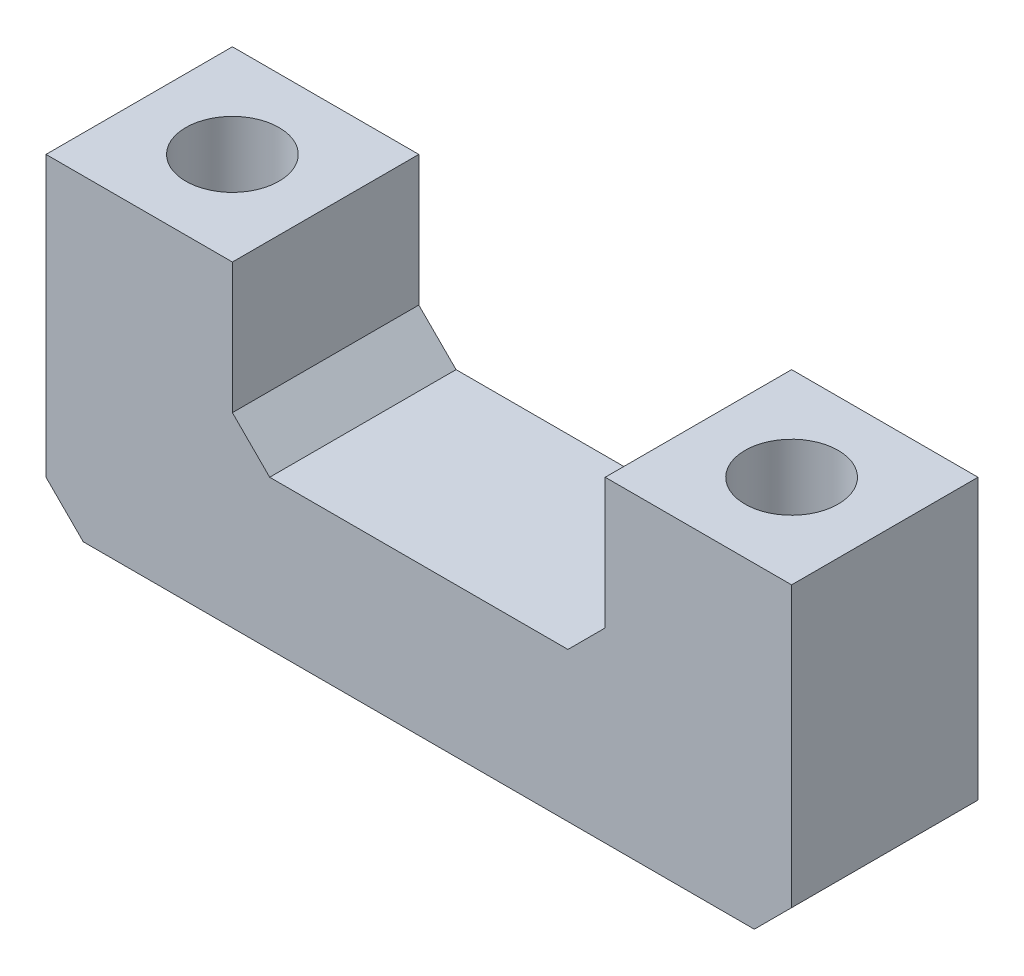
SolidWorks part; units mm, degrees
material "合金钢"
ref_plane "前视基准面" through (0, 0, 0) normal (0, 0, 1) x (1, 0, 0)
ref_plane "上视基准面" through (0, 0, 0) normal (0, 1, 0) x (1, 0, 0)
ref_plane "右视基准面" through (0, 0, 0) normal (1, 0, 0) x (0, 0, -1)
sketch "草图1" plane through (0, 0, 0) normal (0, 0, 1) x (1, 0, 0)
  line L0 (0, 19.9509) -> (0, -14.6445) construction
  line L1 (-22.2139, 0) -> (22.7341, 0) construction
  line L2 (-5, -4.5) -> (5, -4.5)
  line L3 (5, -4.5) -> (5, 0)
  line L4 (5, 0) -> (10, 0)
  line L5 (10, 0) -> (10, -8.5)
  line L6 (10, -8.5) -> (-10, -8.5)
  line L7 (-10, 0) -> (-10, -8.5)
  line L8 (-5, 0) -> (-10, 0)
  line L9 (-5, -4.5) -> (-5, 0)
  point P5 (0, -8.5)
  point P15 (0, -4.5)
  dimension "D1" = 4.5
  dimension "D2" = 4
  dimension "D3" = 5
  dimension "D4" = 10
extrude "凸台-拉伸1" add sketch "草图1" along normal mid plane 5
sketch "草图2" plane through (0, -8.5, 0) normal (0, -1, 0) x (1, 0, 0)
  line L0 (0, 13.43) -> (0, -10.9356) construction
  line L1 (-15.7728, 0) -> (16.7176, 0) construction
  point P5 (-7.5, 0)
  point P6 (7.5, 0)
  dimension "D1" = 15
hole_wizard "M3 螺纹孔1" positions "草图3" profile "草图4" tap size "M3" standard "GB" end condition through all
sketch "草图3" plane through (0, -8.5, 0) normal (0, -1, 0) x (-1, 0, 0)
  point P0 (7.5, 0)
  point P3 (-7.5, 0)
sketch "草图4" plane through (-7.5, -8.5, 0) normal (1, 0, 0) x (0, 0, -1)
  line L0 (0, 0) -> (0, 8.5)
  line L1 (0, 8.5) -> (1.25, 8.5)
  line L2 (1.25, 8.5) -> (1.25, 0)
  line L5 (1.25, 0) -> (0, 0)
  line L11 (0, -6.35) -> (0, 107.95) construction
  dimension "通孔螺纹孔钻头直径" = 2.5
  dimension "通孔螺纹孔钻头深度" = 8.5
cosmetic thread "孔螺蚊线1" parameters "D2"=3
cosmetic thread "孔螺蚊线2" parameters "D2"=3
chamfer "倒角1" distance 1 angle 45 4 edges at (5, -4.5, 0) (-5, -4.5, 0) (10, -8.5, 0) (-10, -8.5, 0)
move or copy body "实体-移动/复制1" [suppressed] bodies to move or copy 107
